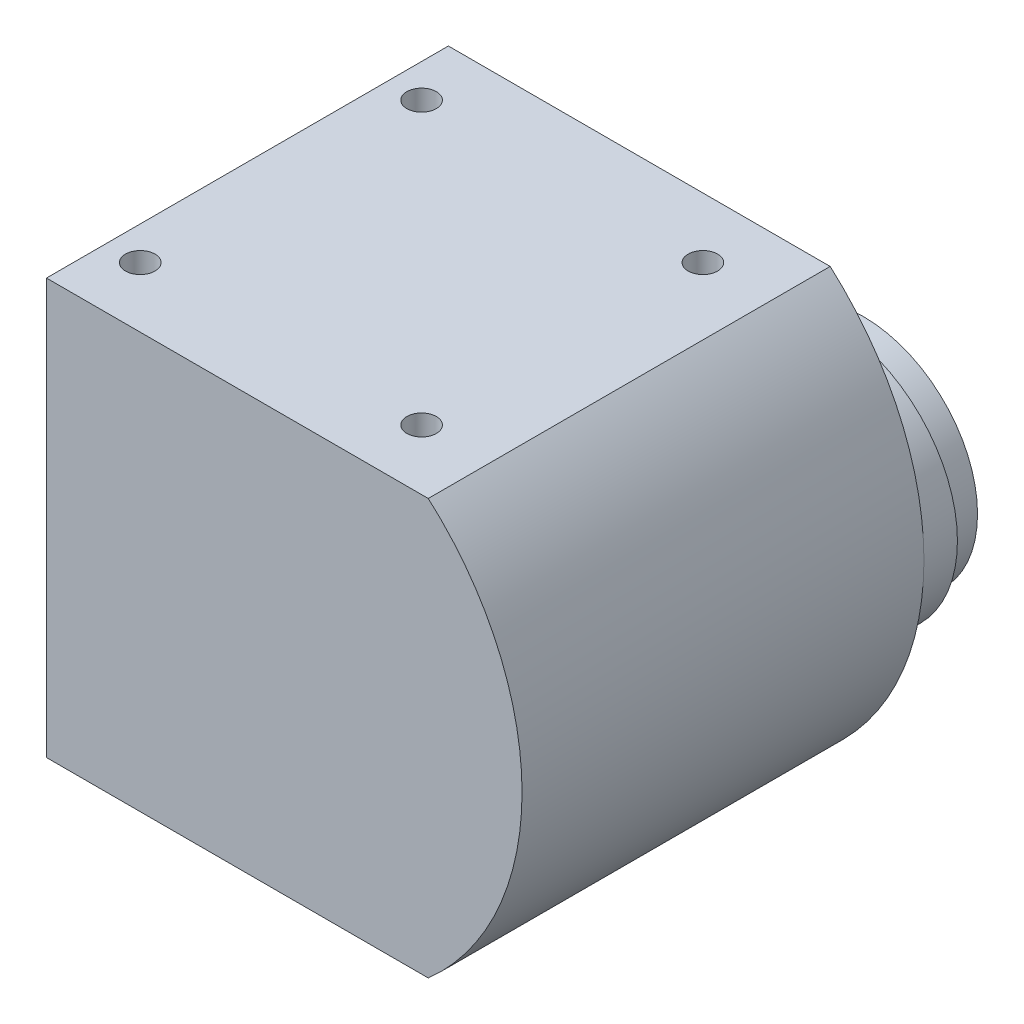
SolidWorks part; units mm, degrees
material "ABS"
ref_plane "正面" through (0, 0, 0) normal (0, 0, 1) x (1, 0, 0)
ref_plane "平面" through (0, 0, 0) normal (0, 1, 0) x (1, 0, 0)
ref_plane "右側面" through (0, 0, 0) normal (1, 0, 0) x (0, 0, -1)
sketch "ｽｹｯﾁ1" plane through (0, 0, 0) normal (0, 0, 1) x (1, 0, 0)
  circle A0 centre (0, 0) radius 8.5
  dimension "D1" = 17
extrude "ﾎﾞｽ - 押し出し1" add sketch "ｽｹｯﾁ1" along normal blind 2.5
sketch "ｽｹｯﾁ2" plane through (0, 0, 2.5) normal (0, 0, 1) x (1, 0, 0)
  circle A0 centre (0, 0) radius 9.5
  dimension "D1" = 19
extrude "ﾎﾞｽ - 押し出し2" add sketch "ｽｹｯﾁ2" along normal blind 2.5
sketch "ｽｹｯﾁ3" plane through (0, 0, 5) normal (0, 0, 1) x (1, 0, 0)
  line L0 (-26, 0) -> (0, 0) construction
  line L1 (-26, 13) -> (0, 13) construction
  line L2 (-26, 13) -> (-26, -13) construction
  line L3 (-26, -13) -> (0, -13) construction
  line L4 (0, 13) -> (0, -13) construction
  line L5 (-26, 15.5) -> (2.5, 15.5)
  line L7 (2.5, -15.5) -> (-26, -15.5)
  line L8 (-26, 15.5) -> (-26, 13)
  line L9 (-26, 13) -> (0, 13)
  line L10 (0, 13) -> (0, -13)
  line L11 (0, -13) -> (-26, -13)
  line L12 (-26, -13) -> (-26, -15.5)
  circle A0 centre (0, 0) radius 17.5 construction
  arc A1 (2.5, -15.5) -> (2.5, 15.5) centre (-11.1607, 0) ccw
  circle A2 centre (0, 0) radius 9.5 construction
  point P11 (0, 0)
  point P15 (0, 0)
  dimension "D1" = 35
  dimension "D3" = 2.5
  dimension "D2" = 26
  dimension "D4" = 2.5
  dimension "D5" = 2.5
extrude "ﾎﾞｽ - 押し出し3" add sketch "ｽｹｯﾁ3" along normal blind 28
sketch "ｽｹｯﾁ4" plane through (0, 0, 5) normal (0, 0, -1) x (-1, 0, 0)
  line L1 (0, 13) -> (26, 13)
  line L2 (0, 13) -> (0, -13)
  line L3 (0, -13) -> (26, -13)
  line L4 (26, 13) -> (26, -13)
extrude "ﾎﾞｽ - 押し出し5" add sketch "ｽｹｯﾁ4" against normal blind 2
sketch "ｽｹｯﾁ6" plane through (0, 0, 33) normal (0, 0, 1) x (1, 0, 0)
  line L0 (-26, 15.5) -> (-26, -15.5)
  line L7 (-26, 13) -> (0, 13)
  line L8 (0, 13) -> (0, -13)
  line L9 (0, -13) -> (-26, -13)
  line L10 (-26, -13) -> (-26, -15.5)
  line L11 (-26, -15.5) -> (2.5, -15.5)
  line L12 (2.5, 15.5) -> (-26, 15.5)
  line L13 (-26, 15.5) -> (-26, 13)
  line L14 (-26, 13) -> (0, 13) construction
  line L15 (0, 13) -> (0, -13) construction
  line L16 (0, -13) -> (-26, -13) construction
  line L17 (-26, -13) -> (-26, -15.5) construction
  line L18 (-26, -15.5) -> (2.5, -15.5)
  line L19 (2.5, 15.5) -> (-26, 15.5)
  line L20 (-26, 15.5) -> (-26, 13) construction
  arc A1 (2.5, -15.5) -> (2.5, 15.5) centre (-11.1607, 0) ccw
  arc A2 (2.5, -15.5) -> (2.5, 15.5) centre (-11.1607, 0) ccw
  dimension "D1" = 0
extrude "ﾎﾞｽ - 押し出し6" add sketch "ｽｹｯﾁ6" along normal blind 2
sketch "ｽｹｯﾁ7" plane through (0, 15.5, 0) normal (0, 1, 0) x (1, 0, 0)
  line L0 (-26, -20) -> (0, -20) construction
  line L1 (-13, -7) -> (-13, -33) construction
  line L3 (-23.5, -9.5) -> (-2.5, -9.5) construction
  line L4 (0, -7) -> (-26, -7)
  line L5 (-26, -7) -> (-26, -33)
  line L6 (-26, -33) -> (0, -33)
  line L7 (0, -33) -> (0, -7)
  line L8 (0, -7) -> (-26, -7) construction
  line L9 (-26, -7) -> (-26, -33) construction
  line L10 (-26, -33) -> (0, -33) construction
  line L11 (0, -33) -> (0, -7) construction
  line L12 (-23.5, -9.5) -> (-23.5, -30.5) construction
  line L13 (-23.5, -30.5) -> (-2.5, -30.5) construction
  line L14 (-2.5, -9.5) -> (-2.5, -30.5) construction
  line L15 (-23.5, -9.5) -> (-2.5, -30.5) construction
  line L16 (-23.5, -30.5) -> (-2.5, -9.5) construction
  circle A0 centre (-23.5, -9.5) radius 1.1
  circle A1 centre (-2.5, -9.5) radius 1.1
  circle A2 centre (-2.5, -30.5) radius 1.1
  circle A3 centre (-23.5, -30.5) radius 1.1
  point P8 (-13, -20)
  point P14 (0, 0)
  point P23 (-13, -20)
  dimension "D4" = 2.2
  dimension "D2" = 21
  dimension "D3" = 21
  dimension "D1" = 0
extrude "ｶｯﾄ - 押し出し1" cut sketch "ｽｹｯﾁ7" against normal through all
